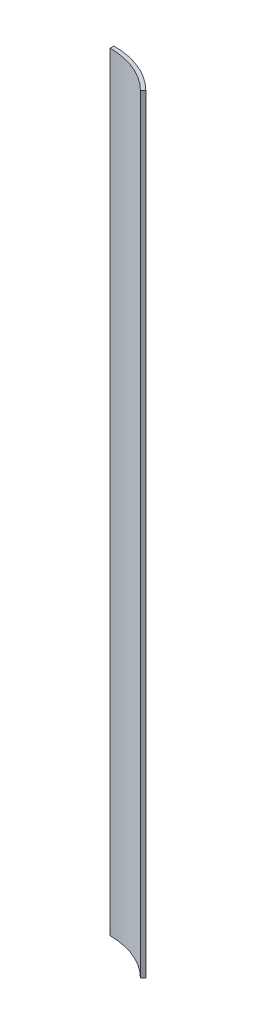
SolidWorks part; units mm, degrees
ref_plane "Front Plane" through (0, 0, 0) normal (0, 0, 1) x (1, 0, 0)
ref_plane "Top Plane" through (0, 0, 0) normal (0, 1, 0) x (1, 0, 0)
ref_plane "Right Plane" through (0, 0, 0) normal (1, 0, 0) x (0, 0, -1)
sketch "Sketch1" plane through (0, 0, 0) normal (0, 1, 0) x (1, 0, 0)
  line L0 (0, 24.13) -> (0, 25.4)
  line L1 (17.0625, 17.0625) -> (17.9605, 17.9605)
  line L2 (0, 0) -> (0, 25.4) construction
  line L3 (0, 0) -> (17.9605, 17.9605) construction
  arc A0 (0, 25.4) -> (17.9605, 17.9605) centre (0, 0) cw
  arc A1 (0, 24.13) -> (17.0625, 17.0625) centre (0, 0) cw
  point P0 (0, 24.8701)
  dimension "D2" = 25.4
  dimension "D3" = 24.13
  dimension "D1" = 45
extrude "Boss-Extrude2" add sketch "Sketch1" along normal blind 254
